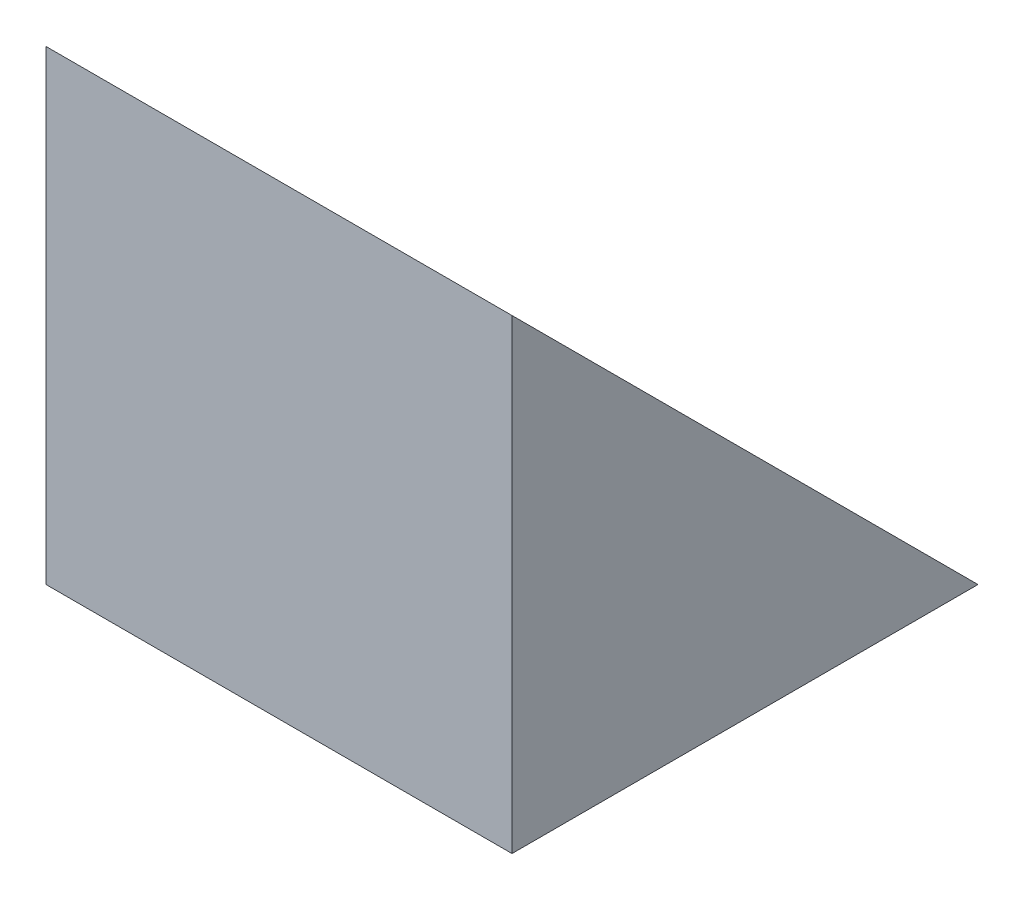
SolidWorks part; units mm, degrees
ref_plane "Front Plane" through (0, 0, 0) normal (0, 0, 1) x (1, 0, 0)
ref_plane "Top Plane" through (0, 0, 0) normal (0, 1, 0) x (1, 0, 0)
ref_plane "Right Plane" through (0, 0, 0) normal (1, 0, 0) x (0, 0, -1)
sketch "Sketch1" plane through (0, 0, 0) normal (1, 0, 0) x (0, 0, -1)
  line L0 (0, 0) -> (0, 40)
  line L1 (0, 55) -> (0, -55) construction
  line L2 (0, 40) -> (40, 0)
  line L3 (55, 0) -> (-55, 0) construction
  line L4 (40, 0) -> (0, 0)
  dimension "D1" = 40
extrude "Boss-Extrude1" add sketch "Sketch1" along normal blind 40
ref_plane "Plane1" through (0, 0, -40) normal (0, 0, 1) x (1, 0, 0)
sketch "Sketch3" plane through (0, 0, -40) normal (0, 0, 1) x (1, 0, 0)
  line L0 (40, 40) -> (0, 40) construction
  line L1 (38, 40) -> (2, 40)
  line L2 (38, 40) -> (38, 2)
  line L3 (38, 2) -> (2, 2)
  line L4 (2, 40) -> (2, 2)
  line L5 (38, 40) -> (2, 2) construction
  line L6 (38, 2) -> (2, 40) construction
  line L7 (40, 0) -> (0, 0) construction
  line L8 (40, 0) -> (40, 40) construction
  point P0 (20, 21)
  point P5 (2.949, 1.928)
  point P10 (20, 0)
  dimension "D1" = 2
  dimension "D2" = 2
extrude "Cut-Extrude1" cut sketch "Sketch3" along normal blind 36
sketch "Sketch4" plane through (0, 2, 0) normal (0, 1, 0) x (1, 0, 0)
  line L0 (38, 38) -> (2, 38) construction
  line L1 (38, 4) -> (38, 38) construction
  circle A0 centre (20, 21) radius 3
  point P2 (0, 0)
  point P5 (20, 38)
  point P6 (0, 0)
  point P9 (38, 21)
  dimension "D1" = 6
extrude "Cut-Extrude2" cut sketch "Sketch4" against normal up to next
